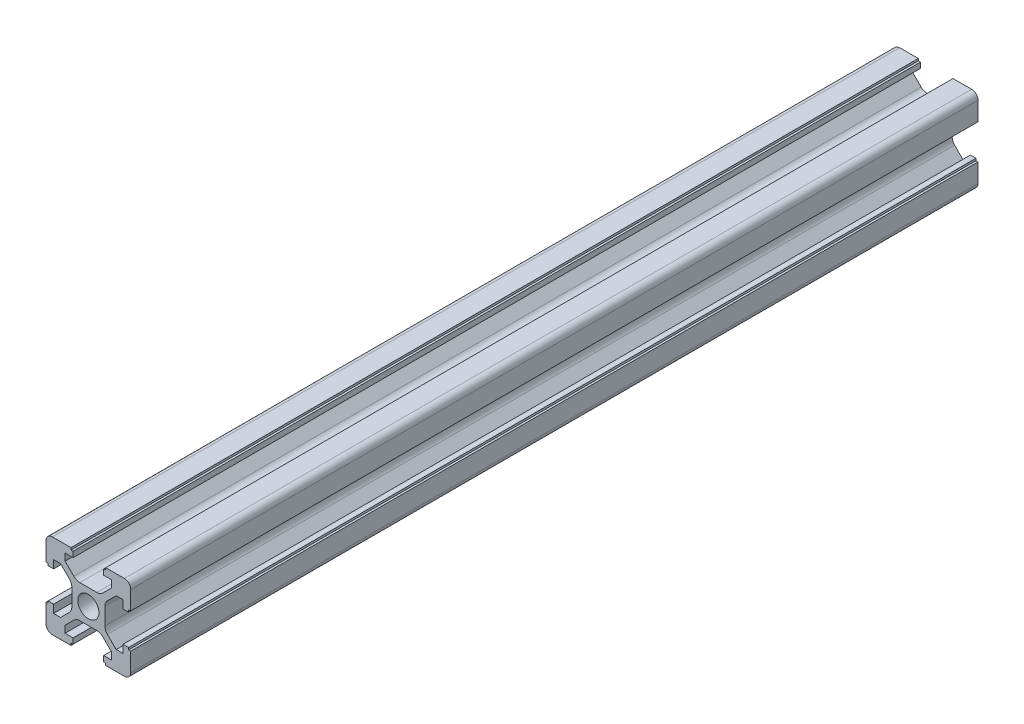
SolidWorks part; units mm, degrees
ref_plane "Front Plane" through (0, 0, 0) normal (0, 0, 1) x (1, 0, 0)
ref_plane "Top Plane" through (0, 0, 0) normal (0, 1, 0) x (1, 0, 0)
ref_plane "Right Plane" through (0, 0, 0) normal (1, 0, 0) x (0, 0, -1)
sketch "Sketch1" plane through (0, 0, 0) normal (0, 0, 1) x (1, 0, 0)
  line L0 (10, -4.1) -> (10, -8.5)
  line L1 (4.1, 10) -> (8.5, 10)
  line L2 (8.5, -10) -> (4.1, -10)
  line L3 (-8.5, -10) -> (-4.1, -10)
  line L4 (10, 8.5) -> (10, 4.1)
  line L7 (8.5, 10) -> (4.1, 10)
  line L8 (5.5, 6.5607) -> (3.4251, 4.4858)
  line L9 (8.5, 10) -> (4.1, 10)
  line L10 (3.9, 2.0109) -> (3.9, -2.0109)
  line L11 (2.0109, -3.9) -> (-2.0109, -3.9)
  line L12 (-3.9, -2.0109) -> (-3.9, 2.0109)
  line L13 (-2.0109, 3.9) -> (2.8393, 3.9)
  line L14 (2.5, 0) -> (22.2403, 0) construction
  line L15 (3.6, 9.5) -> (3.6, 8.2)
  line L16 (9.5, 3.6) -> (8.2, 3.6)
  line L17 (8.2, 3.6) -> (8.2, 5.5)
  line L18 (8.2, 5.5) -> (6.5607, 5.5)
  line L19 (10, -4.1) -> (10, -8.5)
  line L20 (4.1, 9.5) -> (3.6, 9.5)
  line L21 (4.1, 10) -> (4.1, 9.5)
  line L22 (8.5, 10) -> (4.1, 10)
  line L23 (10, 4.1) -> (9.5, 4.1)
  line L24 (9.5, 4.1) -> (9.5, 3.6)
  line L25 (5.5, 8.2) -> (5.5, 6.5607)
  line L26 (3.6, 8.2) -> (5.5, 8.2)
  line L27 (4.4858, 3.4251) -> (6.5607, 5.5)
  line L28 (10, -8.5) -> (10, -4.1)
  line L29 (6.5607, -5.5) -> (4.4858, -3.4251)
  line L30 (10, -8.5) -> (10, -4.1)
  line L31 (2.0109, -3.9) -> (-2.0109, -3.9)
  line L32 (3.9, 2.8393) -> (3.9, -2.0109)
  line L33 (9.5, -3.6) -> (8.2, -3.6)
  line L34 (3.6, -9.5) -> (3.6, -8.2)
  line L35 (3.6, -8.2) -> (5.5, -8.2)
  line L36 (5.5, -8.2) -> (5.5, -6.5607)
  line L37 (9.5, -4.1) -> (9.5, -3.6)
  line L38 (10, -4.1) -> (9.5, -4.1)
  line L39 (10, -8.5) -> (10, -4.1)
  line L40 (4.1, -10) -> (4.1, -9.5)
  line L41 (4.1, -9.5) -> (3.6, -9.5)
  line L42 (8.2, -5.5) -> (6.5607, -5.5)
  line L43 (8.2, -3.6) -> (8.2, -5.5)
  line L44 (3.4251, -4.4858) -> (5.5, -6.5607)
  line L45 (-4.1, -10) -> (-8.5, -10)
  line L46 (-10, -8.5) -> (-10, -4.1)
  line L47 (-8.5, -10) -> (-4.1, -10)
  line L48 (-5.5, -6.5607) -> (-3.4251, -4.4858)
  line L49 (-8.5, -10) -> (-4.1, -10)
  line L50 (-3.9, -2.0109) -> (-3.9, 2.0109)
  line L51 (2.0109, -3.9) -> (-2.0109, -3.9)
  line L52 (-3.6, -9.5) -> (-3.6, -8.2)
  line L53 (-9.5, -3.6) -> (-8.2, -3.6)
  line L54 (-8.2, -3.6) -> (-8.2, -5.5)
  line L55 (-8.2, -5.5) -> (-6.5607, -5.5)
  line L56 (-4.1, -9.5) -> (-3.6, -9.5)
  line L57 (-4.1, -10) -> (-4.1, -9.5)
  line L58 (-8.5, -10) -> (-4.1, -10)
  line L59 (-10, -4.1) -> (-9.5, -4.1)
  line L60 (-9.5, -4.1) -> (-9.5, -3.6)
  line L61 (-5.5, -8.2) -> (-5.5, -6.5607)
  line L62 (-3.6, -8.2) -> (-5.5, -8.2)
  line L63 (-4.4858, -3.4251) -> (-6.5607, -5.5)
  line L64 (-10, 4.1) -> (-10, 8.5)
  line L65 (-8.5, 10) -> (-4.1, 10)
  line L66 (-10, 8.5) -> (-10, 4.1)
  line L67 (-6.5607, 5.5) -> (-4.4858, 3.4251)
  line L68 (-10, 8.5) -> (-10, 4.1)
  line L69 (-2.0109, 3.9) -> (2.0109, 3.9)
  line L70 (-3.9, -2.0109) -> (-3.9, 2.0109)
  line L71 (-9.5, 3.6) -> (-8.2, 3.6)
  line L72 (-3.6, 9.5) -> (-3.6, 8.2)
  line L73 (-3.6, 8.2) -> (-5.5, 8.2)
  line L74 (-5.5, 8.2) -> (-5.5, 6.5607)
  line L75 (-9.5, 4.1) -> (-9.5, 3.6)
  line L76 (-10, 4.1) -> (-9.5, 4.1)
  line L77 (-10, 8.5) -> (-10, 4.1)
  line L78 (-4.1, 10) -> (-4.1, 9.5)
  line L79 (-4.1, 9.5) -> (-3.6, 9.5)
  line L80 (-8.2, 5.5) -> (-6.5607, 5.5)
  line L81 (-8.2, 3.6) -> (-8.2, 5.5)
  line L82 (-3.4251, 4.4858) -> (-5.5, 6.5607)
  line L83 (4.1, -10) -> (8.5, -10)
  arc A0 (2.0109, -3.9) -> (3.4251, -4.4858) centre (2.0109, -5.9) cw
  arc A1 (4.4858, -3.4251) -> (3.9, -2.0109) centre (5.9, -2.0109) cw
  arc A2 (3.9, 2.0109) -> (4.4858, 3.4251) centre (5.9, 2.0109) cw
  arc A3 (2.0109, 3.9) -> (3.4251, 4.4858) centre (2.0109, 5.9) ccw
  arc A4 (-2.0109, 3.9) -> (-3.4251, 4.4858) centre (-2.0109, 5.9) cw
  arc A5 (-4.4858, 3.4251) -> (-3.9, 2.0109) centre (-5.9, 2.0109) cw
  arc A6 (-3.4251, -4.4858) -> (-2.0109, -3.9) centre (-2.0109, -5.9) cw
  arc A7 (-3.9, -2.0109) -> (-4.4858, -3.4251) centre (-5.9, -2.0109) cw
  circle A8 centre (0, 0) radius 2.5
  arc A9 (-8.5, -10) -> (-10, -8.5) centre (-8.5, -8.5) cw
  arc A10 (-10, 8.5) -> (-8.5, 10) centre (-8.5, 8.5) cw
  arc A11 (8.5, 10) -> (10, 8.5) centre (8.5, 8.5) cw
  arc A12 (8.5, -10) -> (10, -8.5) centre (8.5, -8.5) ccw
  point P0 (0, 0)
  point P86 (0, 0)
  point P107 (10, -10)
  dimension "D3" = 2
  dimension "D5" = 5
  dimension "D2" = 1.5
  dimension "D8" = 1.5
  dimension "D4" = 6.1
  dimension "D6" = 20
  dimension "D7" = 6.1
  dimension "D9" = 20
  dimension "D11" = 0.5
  dimension "D12" = 0.5
extrude "Boss-Extrude2" add sketch "Sketch1" along normal blind 200
